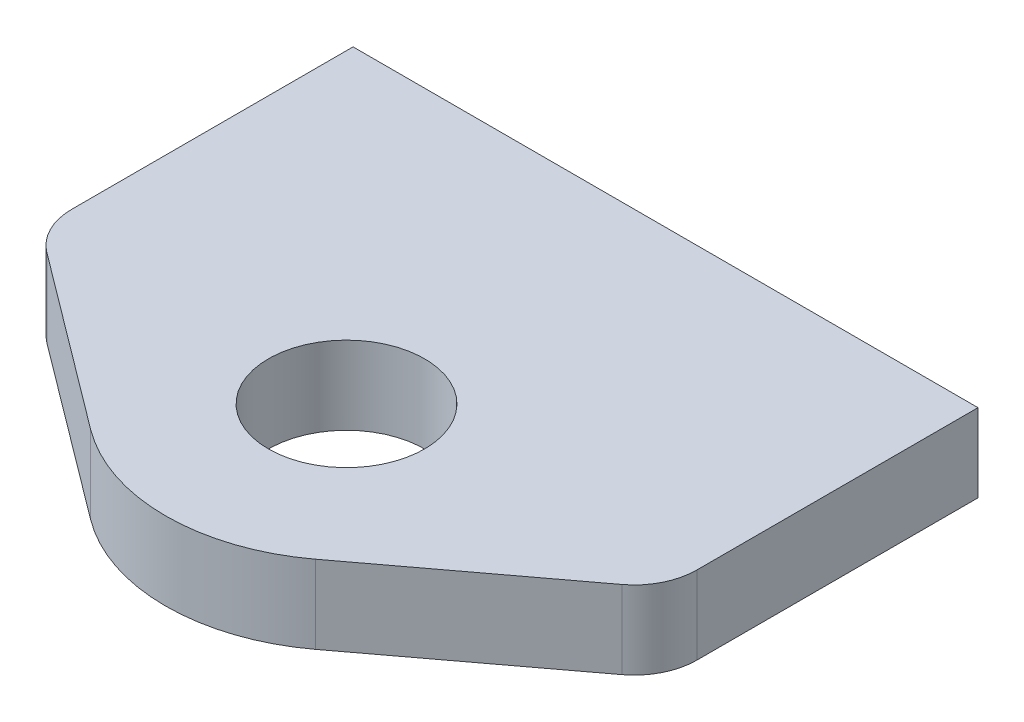
SolidWorks part; units mm, degrees
ref_plane "Front Plane" through (0, 0, 0) normal (0, 0, 1) x (1, 0, 0)
ref_plane "Top Plane" through (0, 0, 0) normal (0, 1, 0) x (1, 0, 0)
ref_plane "Right Plane" through (0, 0, 0) normal (1, 0, 0) x (0, 0, -1)
sketch "Sketch1" plane through (0, 0, 0) normal (0, 1, 0) x (1, 0, 0)
  line L2 (-12.7, -6.35) -> (-12.7, 6.35)
  line L3 (-12.7, 6.35) -> (12.7, 6.35)
  line L4 (12.7, -6.35) -> (12.7, 6.35)
  line L5 (-12.7, -6.35) -> (12.7, 6.35) construction
  line L6 (-12.7, 6.35) -> (12.7, -6.35) construction
  line L11 (-12.7, -6.35) -> (0, -15.875)
  line L12 (0, -15.875) -> (12.7, -6.35)
  line L13 (0, -15.875) -> (-0.2667, -9.525) construction
  circle A0 centre (-0.2667, -6.35) radius 3.175
  point P0 (0, 0)
  point P8 (12.7, 6.35)
  dimension "D3" = 6.35
  dimension "D4" = 6.35
  dimension "D1" = 25.4
  dimension "D2" = 12.7
  dimension "D5" = 9.525
  dimension "D6" = 12.7
extrude "Boss-Extrude1" add sketch "Sketch1" along normal blind 3.175
fillet "Fillet1" radius 7.62 1 edges at (0, 1.5875, 15.875)
fillet "Fillet2" radius 2.54 2 edges at (-12.7, 1.5875, 6.35) (12.7, 1.5875, 6.35)
